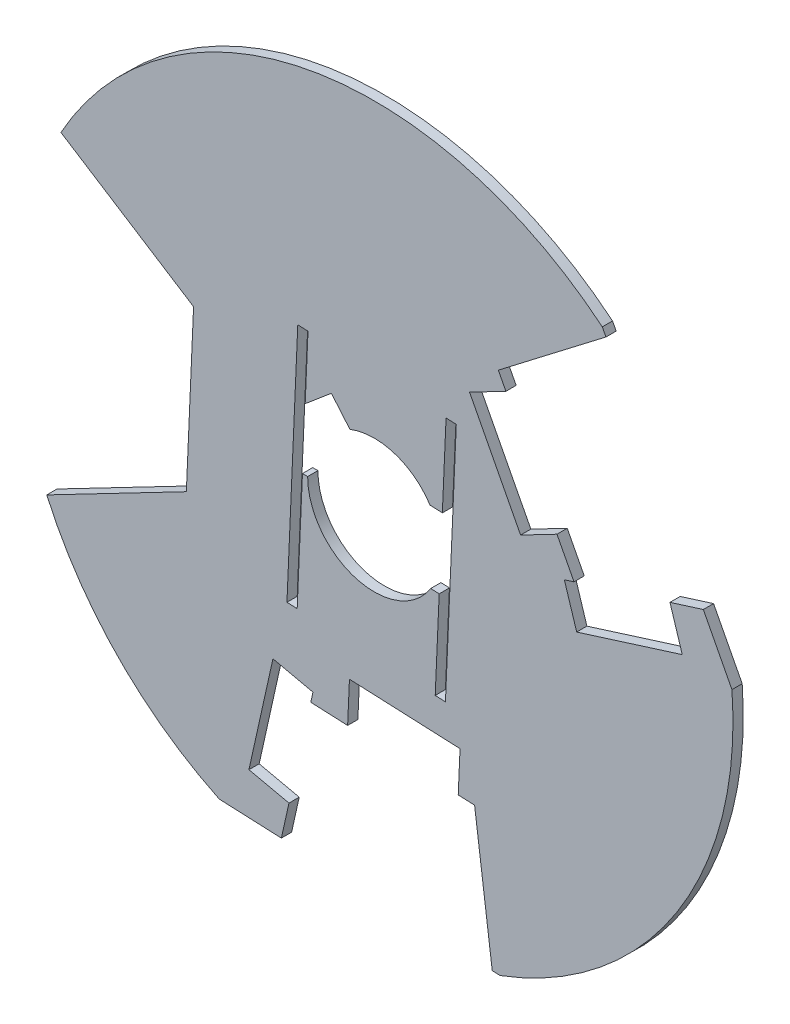
SolidWorks part; units mm, degrees
material "Balsa"
ref_plane "Plan de face" through (0, 0, 0) normal (0, 0, 1) x (1, 0, 0)
ref_plane "Plan de dessus" through (0, 0, 0) normal (0, 1, 0) x (1, 0, 0)
ref_plane "Plan de droite" through (0, 0, 0) normal (1, 0, 0) x (0, 0, -1)
sketch "Esquisse1" plane through (0, 0, 0) normal (0, 0, 1) x (1, 0, 0)
  line L0 (-11.9, 30.243) -> (-20.9197, 40.9503)
  line L1 (0, 0) -> (31.6699, 0) construction
  line L2 (-20.9197, 40.9503) -> (-33.7021, 30.1824)
  line L3 (174.4814, 13.462) -> (160.5092, 40.3333)
  line L4 (0, 0) -> (0, 32.5) construction
  line L5 (35.6001, -41.61) -> (34.7183, -61.5906) construction
  line L6 (-41.7246, -38.1976) -> (-36.7295, -38.418) construction
  line L7 (-41.7246, -38.1976) -> (-41.2837, -28.2073) construction
  line L8 (-41.2837, -28.2073) -> (-36.2886, -28.4277) construction
  line L9 (-36.7295, -38.418) -> (-36.2886, -28.4277) construction
  line L10 (34.7183, -61.5906) -> (40.0089, 58.2928)
  line L11 (-38.9773, 25.7386) -> (-11.9, 30.243) construction
  line L12 (-29.9576, 15.0314) -> (-20.9197, 40.9503) construction
  line L13 (0, 0) -> (-25.4386, 27.9908) construction
  line L14 (34.7183, -61.5906) -> (29.7232, -61.3701)
  line L15 (40.0089, 58.2928) -> (35.0138, 58.5132)
  line L16 (30.605, -41.3896) -> (35.6001, -41.61) construction
  line L17 (30.605, -41.3896) -> (31.0459, -31.3993) construction
  line L18 (35.6001, -41.61) -> (36.041, -31.6197) construction
  line L19 (31.0459, -31.3993) -> (36.041, -31.6197) construction
  line L20 (29.7232, -61.3701) -> (31.6607, -17.466)
  line L21 (-37.6113, -58.3986) -> (-42.6064, -58.1781)
  line L22 (-37.6113, -58.3986) -> (-35.0341, 0)
  line L23 (-42.6064, -58.1781) -> (-37.3158, 61.7052)
  line L24 (39.1272, 38.3122) -> (34.132, 38.5327) construction
  line L25 (39.1272, 38.3122) -> (38.6863, 28.3219) construction
  line L26 (34.132, 38.5327) -> (33.6911, 28.5424) construction
  line L27 (38.6863, 28.3219) -> (33.6911, 28.5424) construction
  line L28 (-32.3207, 61.4847) -> (-37.3158, 61.7052)
  line L29 (-38.9068, 25.6548) -> (-38.9773, 25.7386) construction
  line L30 (-38.9002, 25.8036) -> (-38.9773, 25.7386) construction
  line L31 (-33.7021, 30.1824) -> (-32.3207, 61.4847)
  line L32 (-33.2024, 41.5042) -> (-38.1976, 41.7246) construction
  line L33 (-33.2024, 41.5042) -> (-33.6433, 31.5139) construction
  line L34 (-38.1976, 41.7246) -> (-38.6385, 31.7344) construction
  line L35 (-33.6433, 31.5139) -> (-38.6385, 31.7344) construction
  line L36 (33.2038, 17.5) -> (35.0138, 58.5132)
  line L37 (-32.5, 0) -> (-35.0341, 0)
  line L38 (27.2154, 17.7643) -> (33.2038, 17.5)
  line L39 (27.5233, -17.2834) -> (31.6607, -17.466)
  line L40 (-38.1976, 41.7246) -> (39.1272, 38.3122) construction
  line L41 (-38.1976, 41.7246) -> (-41.7246, -38.1976) construction
  line L42 (39.1272, 38.3122) -> (35.6001, -41.61) construction
  line L43 (-41.7246, -38.1976) -> (35.6001, -41.61) construction
  line L44 (160.5092, 40.3333) -> (97.4284, 20.4765)
  line L45 (97.4284, 20.4765) -> (60.5218, 91.4547)
  line L46 (60.5218, 91.4547) -> (113.0069, 131.6888)
  line L47 (113.0069, 131.6888) -> (111.2327, 135.101)
  line L49 (61.3846, -163.8808) -> (57.5424, -163.7113)
  line L50 (57.5424, -163.7113) -> (48.9412, -98.1408)
  line L51 (48.9412, -98.1408) -> (-30.981, -94.6137)
  line L52 (-30.981, -94.6137) -> (-45.325, -159.1716)
  line L53 (-45.325, -159.1716) -> (-75.5823, -157.8364)
  arc A0 (111.2327, 135.101) -> (-75.5823, -157.8364) centre (0, 0) ccw
  arc A1 (-32.5, 0) -> (27.5233, -17.2834) centre (0, 0) ccw
  arc A2 (27.2154, 17.7643) -> (-11.9, 30.243) centre (0, 0) ccw
  arc A3 (61.3846, -163.8808) -> (174.4814, 13.462) centre (0, 0) ccw
  circle A4 centre (121.4843, 17.5652) radius 4.7
  circle A5 centre (67.7962, 55.7884) radius 4.7
  circle A6 centre (14.4161, -86.6074) radius 4.7
  circle A7 centre (-45.5303, -113.9911) radius 4.7
  dimension "D1" = 65
  dimension "D2" = 87.845
  dimension "D3" = 42.265
  dimension "D4" = 14
  dimension "D5" = 10
  dimension "D6" = 57.18
  dimension "D7" = 5
  dimension "D8" = 20
  dimension "D9" = 20
  dimension "D11" = 35
  dimension "D12" = 17.5
extrude "Boss.-Extru.1" add sketch "Esquisse1" along normal blind 5
sketch "Esquisse2" plane through (0, 0, 5) normal (0, 0, 1) x (1, 0, 0)
  line L0 (-88.149, 43.929) -> (-152.8606, 85.1976)
  line L1 (-88.149, 43.929) -> (-91.676, -35.9932)
  line L2 (-91.676, -35.9932) -> (-159.7715, -71.4008)
  line L3 (0, 0) -> (0, 85.1976) construction
  line L5 (0, 0) -> (-89.9125, 3.9679) construction
  circle A0 centre (0, 0) radius 175 construction
  arc A1 (-152.8606, 85.1976) -> (-159.7715, -71.4008) centre (0, 0) ccw
  dimension "D1" = 90
  dimension "D2" = 80
  dimension "D3" = 120
  dimension "D4" = 87.473
extrude "Enlèv. mat.-Extru.1" cut sketch "Esquisse2" against normal blind 10
sketch "Esquisse3" plane through (0, 0, 5) normal (0, 0, 1) x (1, 0, 0)
  line L0 (14.4161, -86.6074) -> (41.3898, -87.7978) construction
  line L1 (48.9412, -98.1408) -> (-30.981, -94.6137) construction
  line L2 (40.949, -97.7881) -> (-12.9985, -95.4073)
  line L3 (40.949, -97.7881) -> (41.8307, -77.8075)
  line L4 (-12.9985, -95.4073) -> (-12.1168, -75.4267)
  line L5 (41.8307, -77.8075) -> (-12.1168, -75.4267)
  line L6 (-45.5303, -113.9911) -> (-39.6741, -87.6339) construction
  line L7 (-30.981, -94.6137) -> (-45.325, -159.1716) construction
  line L8 (-49.436, -85.4649) -> (-29.9121, -89.8028)
  line L9 (-49.436, -85.4649) -> (-61.1485, -138.1794)
  line L10 (-29.9121, -89.8028) -> (-41.6246, -142.5173)
  line L11 (-61.1485, -138.1794) -> (-41.6246, -142.5173)
  line L12 (64.2125, 84.3569) -> (89.1244, 36.4466)
  line L13 (64.2125, 84.3569) -> (46.4679, 75.1302)
  line L14 (89.1244, 36.4466) -> (71.3799, 27.2199)
  line L15 (46.4679, 75.1302) -> (71.3799, 27.2199)
  line L16 (98.7328, -0.0804) -> (92.7276, 18.9968)
  line L17 (98.7328, -0.0804) -> (150.2411, 16.1336)
  line L18 (92.7276, 18.9968) -> (144.2359, 35.2107)
  line L19 (150.2411, 16.1336) -> (144.2359, 35.2107)
  line L20 (67.7962, 55.7884) -> (55.3402, 79.7435) construction
  line L21 (121.4843, 17.5652) -> (95.7302, 9.4582) construction
  line L22 (160.5092, 40.3333) -> (97.4284, 20.4765) construction
  line L23 (97.4284, 20.4765) -> (60.5218, 91.4547) construction
  point P33 (0, 0)
  dimension "D1" = 20
  dimension "D2" = 54
  dimension "D3" = 27
  dimension "D4" = 20
  dimension "D5" = 54
  dimension "D6" = 27
  dimension "D7" = 2
extrude "Enlèv. mat.-Extru.2" cut sketch "Esquisse3" against normal blind 10
